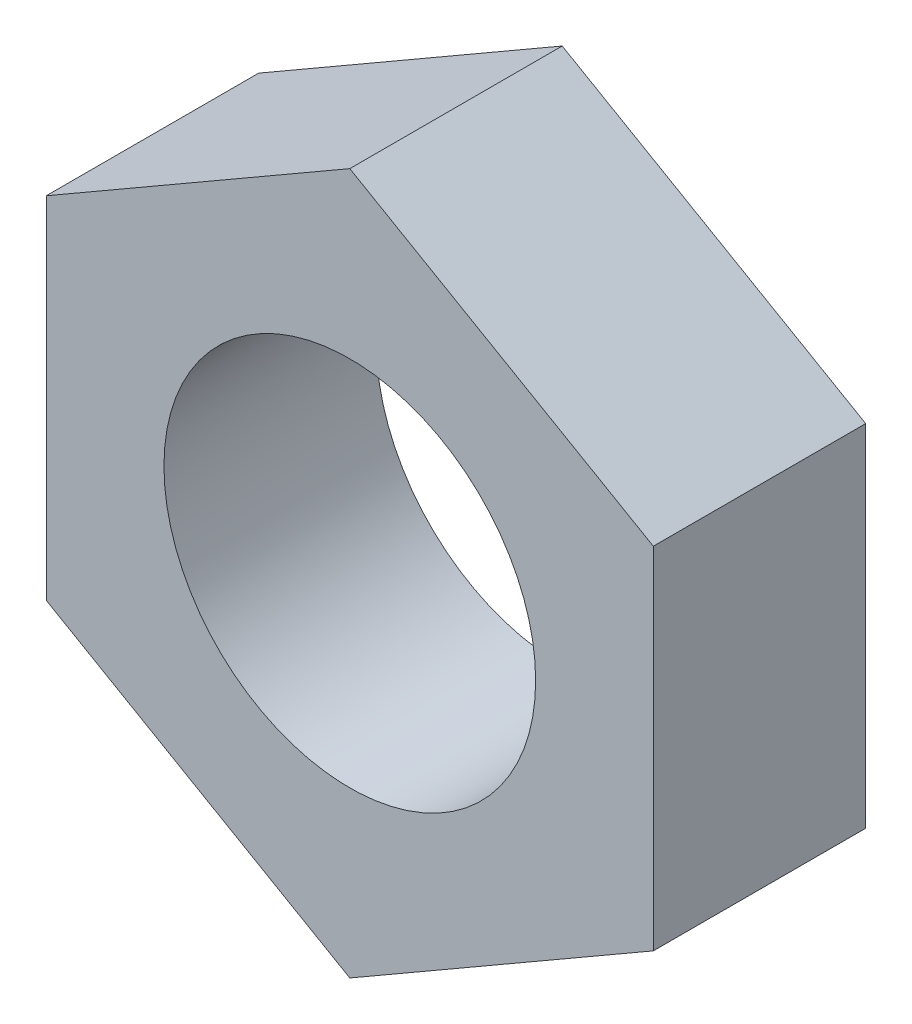
SolidWorks part; units mm, degrees
ref_plane "Plan de face" through (0, 0, 0) normal (0, 0, 1) x (1, 0, 0)
ref_plane "Plan de dessus" through (0, 0, 0) normal (0, 1, 0) x (1, 0, 0)
ref_plane "Plan de droite" through (0, 0, 0) normal (1, 0, 0) x (0, 0, -1)
sketch "Esquisse1" plane through (0, 0, 0) normal (0, 0, 1) x (1, 0, 0)
  line L0 (0, 0) -> (0, 3.3)
  line L2 (0, 3.3) -> (-2.8579, 1.65)
  line L3 (-2.8579, 1.65) -> (-2.8579, -1.65)
  line L4 (-2.8579, -1.65) -> (0, -3.3)
  line L5 (0, -3.3) -> (2.8579, -1.65)
  line L6 (2.8579, -1.65) -> (2.8579, 1.65)
  line L7 (2.8579, 1.65) -> (0, 3.3)
  circle A0 centre (0, 0) radius 2.8579 construction
  circle A1 centre (0, 0) radius 1.75
  dimension "D2" = 3.5
  dimension "D1" = 3.3
extrude "Boss.-Extru.1" add sketch "Esquisse1" along normal blind 2
